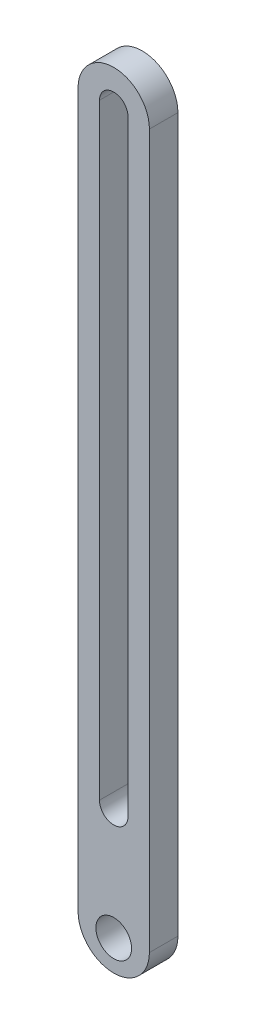
SolidWorks part; units mm, degrees
ref_plane "Front Plane" through (0, 0, 0) normal (0, 0, 1) x (1, 0, 0)
ref_plane "Top Plane" through (0, 0, 0) normal (0, 1, 0) x (1, 0, 0)
ref_plane "Right Plane" through (0, 0, 0) normal (1, 0, 0) x (0, 0, -1)
sketch "Sketch2" plane through (0, 0, 0) normal (0, 0, 1) x (1, 0, 0)
  line L0 (0, 174.9961) -> (0, -25.0039) construction
  line L1 (10, 174.9961) -> (10, -25.0039)
  line L2 (-10, 174.9961) -> (-10, -25.0039)
  line L3 (0, 174.9961) -> (0, 4.9961) construction
  line L4 (4, 174.9961) -> (4, 4.9961)
  line L5 (-4, 174.9961) -> (-4, 4.9961)
  arc A0 (10, 174.9961) -> (-10, 174.9961) centre (0, 174.9961) ccw
  arc A1 (-10, -25.0039) -> (10, -25.0039) centre (0, -25.0039) ccw
  arc A2 (4, 174.9961) -> (-4, 174.9961) centre (0, 174.9961) ccw
  arc A3 (-4, 4.9961) -> (4, 4.9961) centre (0, 4.9961) ccw
  point P3 (0, 74.9961)
  point P9 (0, 184.9961)
  point P10 (0, -35.0039)
  point P12 (0, 89.9961)
  dimension "D1" = 220
  dimension "D2" = 20
extrude "Boss-Extrude1" add sketch "Sketch2" along normal blind 8
sketch "Sketch3" plane through (0, 0, 8) normal (0, 0, 1) x (1, 0, 0)
  circle A0 centre (0, -26.4825) radius 5
extrude "Cut-Extrude1" cut sketch "Sketch3" against normal blind 8
